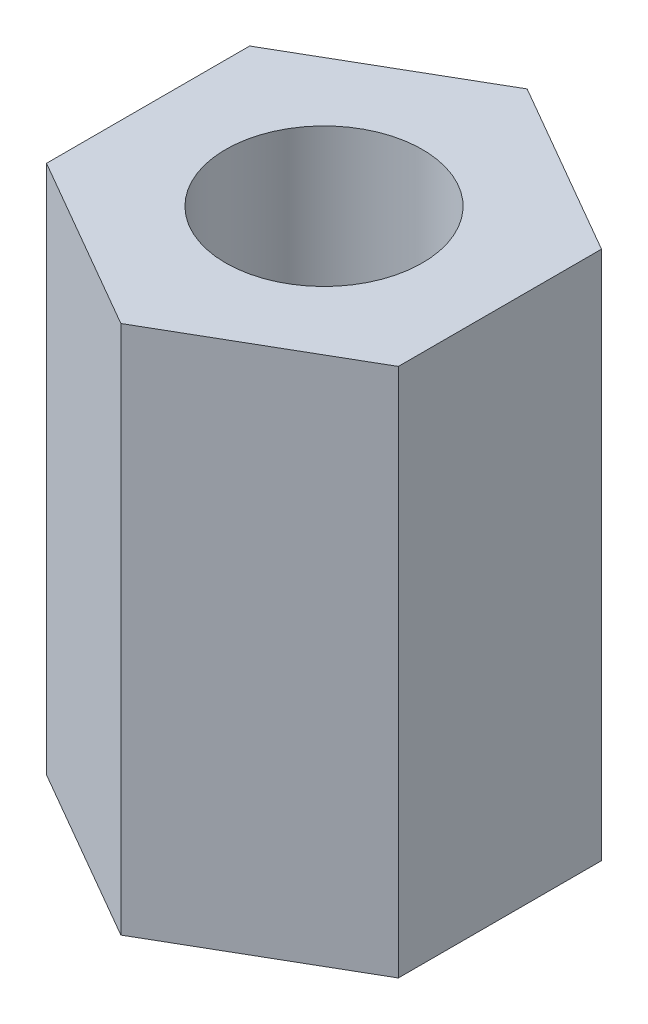
SolidWorks part; units mm, degrees
ref_plane "Front Plane" through (0, 0, 0) normal (0, 0, 1) x (1, 0, 0)
ref_plane "Top Plane" through (0, 0, 0) normal (0, 1, 0) x (1, 0, 0)
ref_plane "Right Plane" through (0, 0, 0) normal (1, 0, 0) x (0, 0, -1)
sketch "Sketch1" plane through (0, 0, 0) normal (0, 1, 0) x (1, 0, 0)
  line L1 (0, -2.6847) -> (2.325, -1.3423)
  line L2 (2.325, -1.3423) -> (2.325, 1.3423)
  line L3 (2.325, 1.3423) -> (0, 2.6847)
  line L4 (0, 2.6847) -> (-2.325, 1.3423)
  line L5 (-2.325, 1.3423) -> (-2.325, -1.3423)
  line L6 (-2.325, -1.3423) -> (0, -2.6847)
  circle A0 centre (0, 0) radius 2.325 construction
  circle A1 centre (0, 0) radius 1.3
  dimension "D2" = 2.6
  dimension "D1" = 4.65
extrude "Shape" add sketch "Sketch1" along normal blind 7
equation "\"Height\"=6"
